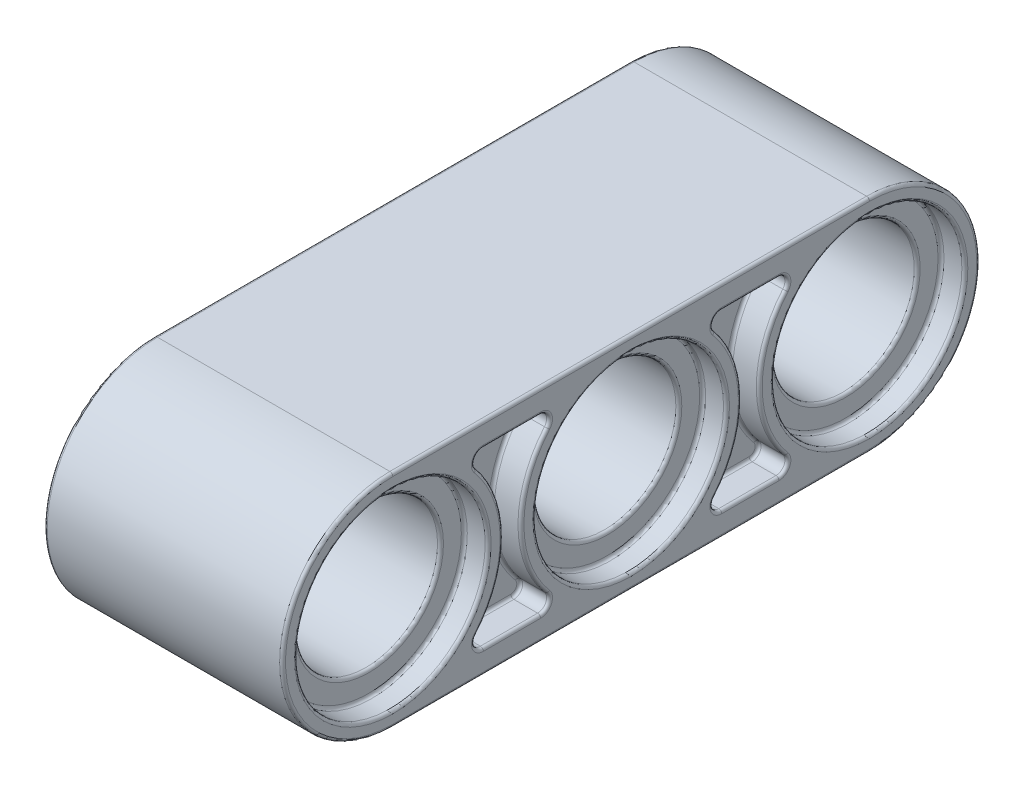
SolidWorks part; units mm, degrees
ref_plane "Front Plane" through (0, 0, 0) normal (0, 0, 1) x (1, 0, 0)
ref_plane "Top Plane" through (0, 0, 0) normal (0, 1, 0) x (1, 0, 0)
ref_plane "Right Plane" through (0, 0, 0) normal (1, 0, 0) x (0, 0, -1)
sketch "Sketch1" plane through (0, 0, 0) normal (1, 0, 0) x (0, 0, -1)
  line L0 (-5.7324, 0) -> (10.2676, 0) construction
  line L1 (-5.7324, 3.7) -> (10.2676, 3.7)
  line L2 (-5.7324, -3.7) -> (10.2676, -3.7)
  arc A0 (-5.7324, 3.7) -> (-5.7324, -3.7) centre (-5.7324, 0) ccw
  arc A1 (10.2676, -3.7) -> (10.2676, 3.7) centre (10.2676, 0) ccw
  circle A2 centre (-5.7324, 0) radius 2.4
  circle A3 centre (2.2676, 0) radius 2.4
  circle A4 centre (10.2676, 0) radius 2.4
  point P3 (2.2676, 0)
  dimension "D3" = 4.8
  dimension "D1" = 7.4
  dimension "D2" = 16
  dimension "D4" = 3
extrude "Boss-Extrude1" add sketch "Sketch1" along normal blind 8
sketch "Sketch2" plane through (8, 0, 0) normal (1, 0, 0) x (0, 0, -1)
  circle A0 centre (-5.7324, 0) radius 3.2
  circle A1 centre (2.2676, 0) radius 3.2
  circle A2 centre (10.2676, 0) radius 3.2
  dimension "D1" = 3
extrude "Cut-Extrude1" cut sketch "Sketch2" against normal blind 0.8
ref_plane "Plane1" through (4, 0, 0) normal (1, 0, 0) x (0, 0, -1)
sketch "Sketch3" plane through (8, 0, 0) normal (1, 0, 0) x (0, 0, -1)
  line L0 (-2.6927, 2.9) -> (-0.7721, 2.9)
  line L1 (10.2676, 3.7) -> (-5.7324, 3.7) construction
  line L2 (2.2676, 0) -> (-5.7324, 0) construction
  line L3 (-2.6927, -2.9) -> (-0.7721, -2.9)
  line L4 (5.3073, 2.9) -> (7.2279, 2.9)
  line L5 (5.3073, -2.9) -> (7.2279, -2.9)
  line L6 (10.2676, 0) -> (2.2676, 0) construction
  arc A0 (-2.9206, -2.405) -> (-2.9206, 2.405) centre (-5.7324, 0) ccw
  arc A1 (-0.5442, 2.405) -> (-0.5442, -2.405) centre (2.2676, 0) ccw
  arc A2 (-2.6927, -2.9) -> (-2.9206, -2.405) centre (-2.6927, -2.6) cw
  arc A3 (-0.7721, -2.9) -> (-0.5442, -2.405) centre (-0.7721, -2.6) ccw
  arc A4 (-0.7721, 2.9) -> (-0.5442, 2.405) centre (-0.7721, 2.6) cw
  arc A5 (-2.6927, 2.9) -> (-2.9206, 2.405) centre (-2.6927, 2.6) ccw
  arc A6 (5.0794, -2.405) -> (5.0794, 2.405) centre (2.2676, 0) ccw
  arc A7 (7.4558, 2.405) -> (7.4558, -2.405) centre (10.2676, 0) ccw
  arc A8 (5.3073, -2.9) -> (5.0794, -2.405) centre (5.3073, -2.6) cw
  arc A9 (7.2279, -2.9) -> (7.4558, -2.405) centre (7.2279, -2.6) ccw
  arc A10 (7.2279, 2.9) -> (7.4558, 2.405) centre (7.2279, 2.6) cw
  arc A11 (5.3073, 2.9) -> (5.0794, 2.405) centre (5.3073, 2.6) ccw
  point P11 (-3.4346, -2.9)
  point P14 (-0.0302, -2.9)
  point P17 (-0.0302, 2.9)
  point P20 (-3.4346, 2.9)
  dimension "D3" = 0.3
  dimension "D2" = 0.8
  dimension "D1" = 2
  dimension "D4" = 2
extrude "Cut-Extrude2" cut sketch "Sketch3" against normal blind 1
mirror "Mirror1" about plane through (4, 0, 0) normal (1, 0, 0) of "Cut-Extrude2", "Cut-Extrude1"
fillet "Fillet1" radius 0.1 90 edges at (0, -2.7255, -5.0349) (0, 0, -5.9676) (0, 2.7255, -5.0349) (0, 2.9, -6.2676) (0, 2.7255, -7.5004) (0, 0, -6.5676) (0, -2.7255, -7.5004) (0, -2.9, -6.2676) (1, -2.7255, -5.0349) (1, 0, -5.9676) (1, 2.7255, -5.0349) (1, 2.9, -6.2676) (1, 2.7255, -7.5004) (1, 0, -6.5676) (1, -2.7255, -7.5004) (1, -2.9, -6.2676) (0, -2.7255, 2.9651) (0, 0, 2.0324) (0, 2.7255, 2.9651) (0, 2.9, 1.7324) (0, 2.7255, 0.4996) (0, 0, 1.4324) (0, -2.7255, 0.4996) (0, -2.9, 1.7324) (1, -2.7255, 2.9651) (1, 0, 2.0324) (1, 2.7255, 2.9651) (1, 2.9, 1.7324) (1, 2.7255, 0.4996) (1, 0, 1.4324) (1, -2.7255, 0.4996) (1, -2.9, 1.7324) (0, 0, -13.4676) (0.8, 0, -13.4676) (0.8, 0, -7.8676) (0, 0, -5.4676) (0.8, 0, 0.1324) (0, 0, 2.5324) (0.8, 0, 2.5324) (0.8, 0, 8.1324) (8, -2.7255, -5.0349) (8, -2.9, -6.2676) (8, -2.7255, -7.5004) (8, 0, -6.5676) (8, 2.7255, -7.5004) (8, 2.9, -6.2676) (8, 2.7255, -5.0349) (8, 0, -5.9676) (7, -2.7255, -5.0349) (7, -2.9, -6.2676) (7, -2.7255, -7.5004) (7, 0, -6.5676) (7, 2.7255, -7.5004) (7, 2.9, -6.2676) (7, 2.7255, -5.0349) (7, 0, -5.9676) (8, -2.7255, 2.9651) (8, -2.9, 1.7324) (8, -2.7255, 0.4996) (8, 0, 1.4324) (8, 2.7255, 0.4996) (8, 2.9, 1.7324) (8, 2.7255, 2.9651) (8, 0, 2.0324) (7, -2.7255, 2.9651) (7, -2.9, 1.7324) (7, -2.7255, 0.4996) (7, 0, 1.4324) (7, 2.7255, 0.4996) (7, 2.9, 1.7324) (7, 2.7255, 2.9651) (7, 0, 2.0324) (8, 0, -13.4676) (7.2, 0, -13.4676) (7.2, 0, -12.6676) (8, 0, -5.4676) (7.2, 0, -5.4676) (7.2, 0, -4.6676) (8, 0, 2.5324) (7.2, 0, 2.5324) (7.2, 0, 3.3324) (0, 0, 9.4324) (0, -3.7, -2.2676) (0, 0, -13.9676) (0, 3.7, -2.2676) (8, 0, 9.4324) (8, -3.7, -2.2676) (8, 0, -13.9676) (8, 3.7, -2.2676) (0.8, 0, -5.4676)
